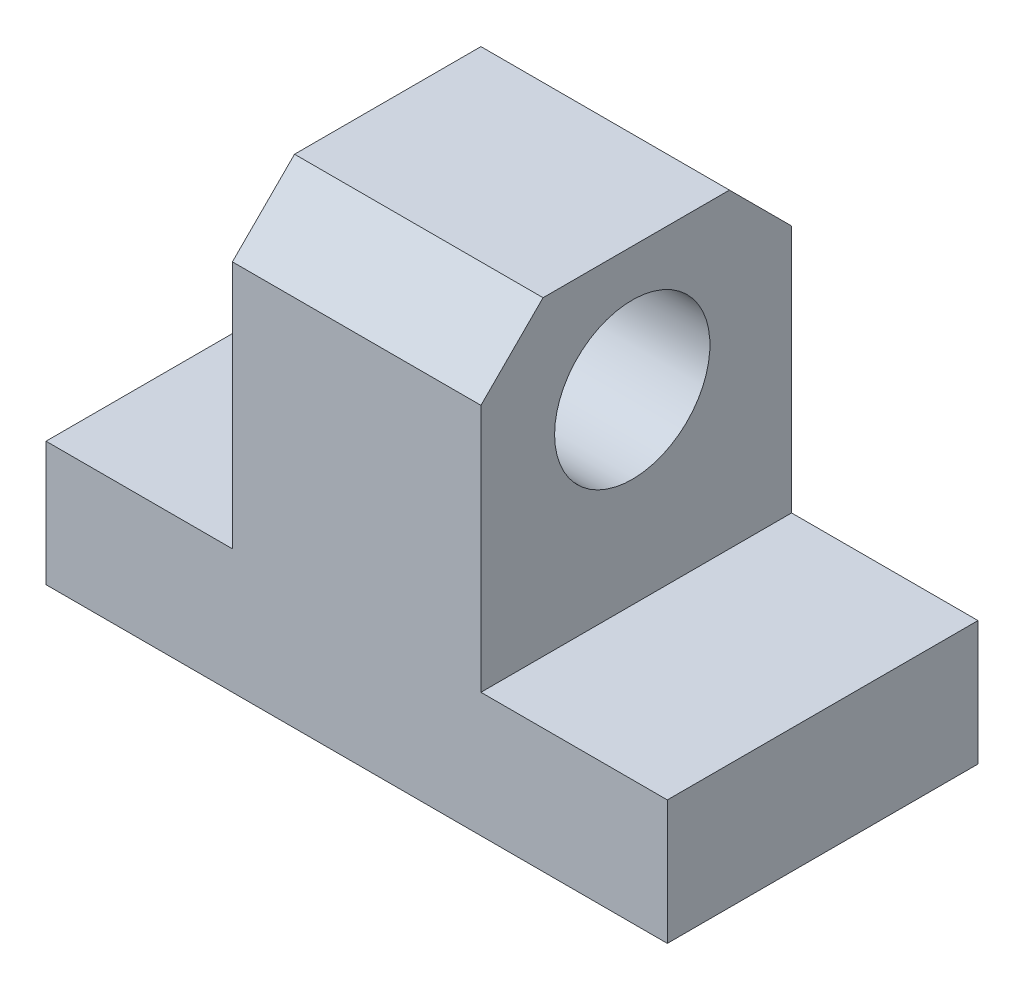
SolidWorks part; units mm, degrees
ref_plane "Спереди" through (0, 0, 0) normal (0, 0, 1) x (1, 0, 0)
ref_plane "Сверху" through (0, 0, 0) normal (0, 1, 0) x (1, 0, 0)
ref_plane "Справа" through (0, 0, 0) normal (1, 0, 0) x (0, 0, -1)
sketch "Эскиз1" plane through (0, 0, 0) normal (0, 1, 0) x (1, 0, 0)
  line L1 (-10, 5) -> (10, 5)
  line L2 (-10, 5) -> (-10, -5)
  line L3 (-10, -5) -> (10, -5)
  line L4 (10, 5) -> (10, -5)
  line L5 (-10, 5) -> (10, -5) construction
  line L6 (-10, -5) -> (10, 5) construction
  point P0 (0, 0)
extrude "Вытянуть1" add sketch "Эскиз1" along normal blind 4
sketch "Эскиз2" plane through (0, 4, 0) normal (0, 1, 0) x (1, 0, 0)
  line L0 (-10, -5) -> (10, -5) construction
  line L1 (-4, 5) -> (4, 5)
  line L2 (-4, 5) -> (-4, -5)
  line L3 (-4, -5) -> (4, -5)
  line L4 (4, 5) -> (4, -5)
  line L5 (-4, 5) -> (4, -5) construction
  line L6 (-4, -5) -> (4, 5) construction
  point P0 (0, 0)
extrude "Вытянуть2" add sketch "Эскиз2" along normal blind 10
sketch "Эскиз3" plane through (-4, 0, 0) normal (-1, 0, 0) x (0, 0, 1)
  circle A0 centre (0.1288, 10) radius 2.5
extrude "Вырез-Вытянуть1" cut sketch "Эскиз3" against normal through all
chamfer "Фаска1" distance 2 angle 45 2 edges at (0, 14, -5) (0, 14, 5)
